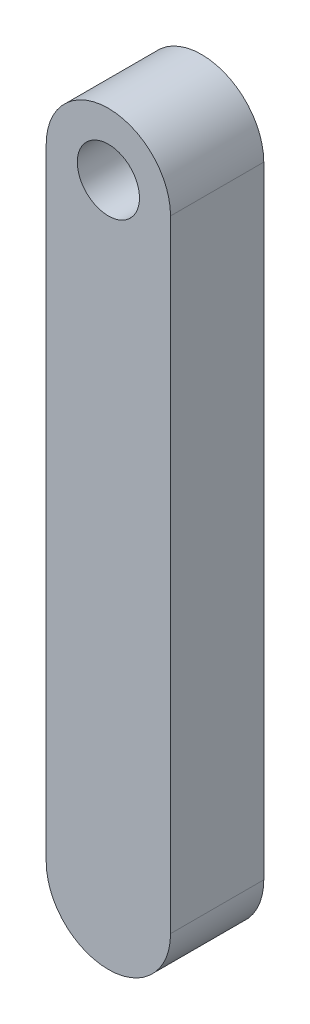
SolidWorks part; units mm, degrees
material "PUR"
ref_plane "Ön Düzlem" through (0, 0, 0) normal (0, 0, 1) x (1, 0, 0)
ref_plane "Üst Düzlem" through (0, 0, 0) normal (0, 1, 0) x (1, 0, 0)
ref_plane "Sağ Düzlem" through (0, 0, 0) normal (1, 0, 0) x (0, 0, -1)
sketch "Çizim1" plane through (0, 0, 0) normal (0, 0, 1) x (1, 0, 0)
  line L0 (-3, 18.9739) -> (-3, -11.0261)
  line L1 (3, 18.9739) -> (3, -11.0261)
  arc A0 (3, 18.9739) -> (-3, 18.9739) centre (0, 18.9739) ccw
  arc A1 (-3, -11.0261) -> (3, -11.0261) centre (0, -11.0261) ccw
  circle A2 centre (0, 18.9739) radius 1.5
  dimension "D1" = 6
  dimension "D3" = 3
  dimension "D2" = 30
extrude "Yükseklik-Ekstrüzyon1" add sketch "Çizim1" along normal blind 4.5
